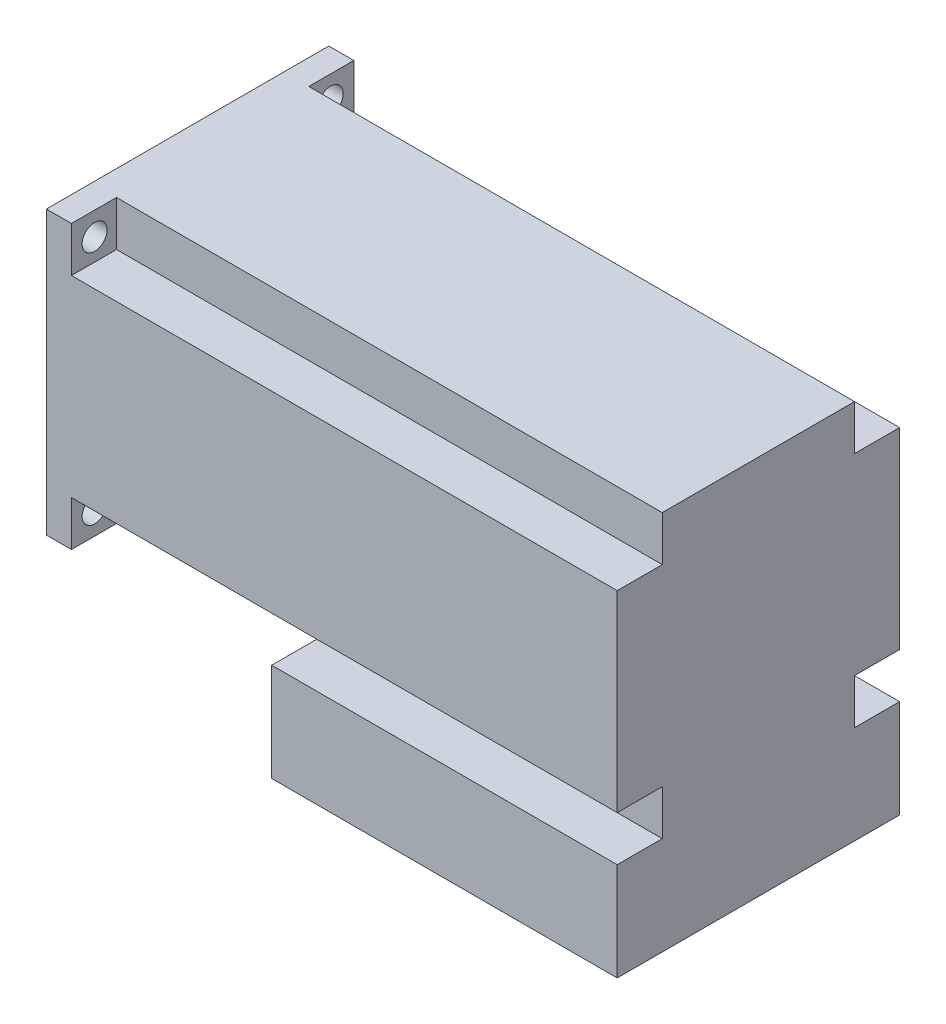
SolidWorks part; units mm, degrees
ref_plane "Front Plane" through (0, 0, 0) normal (0, 0, 1) x (1, 0, 0)
ref_plane "Top Plane" through (0, 0, 0) normal (0, 1, 0) x (1, 0, 0)
ref_plane "Right Plane" through (0, 0, 0) normal (1, 0, 0) x (0, 0, -1)
sketch "Sketch1" plane through (0, 0, 0) normal (0, 0, 1) x (1, 0, 0)
  line L0 (45, 0) -> (45, -19.6)
  line L1 (0, 0) -> (45, 0)
  line L2 (0, 0) -> (0, 56.4)
  line L3 (0, 56.4) -> (114, 56.4)
  line L4 (114, 0) -> (114, 56.4)
  line L5 (45, -19.6) -> (114, -19.6)
  line L6 (114, -19.6) -> (114, 0)
  dimension "D1" = 114
  dimension "D2" = 56.4
  dimension "D3" = 76
  dimension "D4" = 45
extrude "Boss-Extrude1" add sketch "Sketch1" along normal blind 56.4
sketch "Sketch2" plane through (0, 0, 0) normal (-1, 0, 0) x (0, 0, 1)
  line L0 (0, 28.2) -> (56.4, 28.2) construction
  line L1 (0, 56.4) -> (0, 0) construction
  line L2 (56.4, 56.4) -> (56.4, 0) construction
  line L3 (28.2, 28.2) -> (28.2, 0) construction
  line L4 (56.4, 0) -> (0, 0) construction
  circle A0 centre (4.63, 4.63) radius 2.5
  circle A1 centre (51.77, 4.63) radius 2.5
  circle A2 centre (51.77, 51.77) radius 2.5
  circle A3 centre (4.63, 51.77) radius 2.5
  dimension "D1" = 5
  dimension "D4" = 23.57
  dimension "D5" = 23.57
  dimension "D2" = 2
  dimension "D3" = 2
extrude "Cut-Extrude1" cut sketch "Sketch2" against normal blind 5
sketch "Sketch3" plane through (0, 0, 0) normal (-1, 0, 0) x (0, 0, 1)
  line L0 (0, 0) -> (56.4, 56.4) construction
  circle A0 centre (28.2, 28.2) radius 3.175
  dimension "D1" = 6.35
extrude "Boss-Extrude2" add sketch "Sketch3" along normal blind 20
sketch "Sketch4" plane through (114, 0, 0) normal (1, 0, 0) x (0, 0, -1)
  line L1 (-56.4, 56.4) -> (-47.4, 56.4)
  line L2 (-56.4, 56.4) -> (-56.4, 47.4)
  line L3 (-56.4, 47.4) -> (-47.4, 47.4)
  line L4 (-47.4, 56.4) -> (-47.4, 47.4)
  line L16 (-9, 56.4) -> (-9, 47.4)
  line L17 (-9, 56.4) -> (0, 56.4)
  line L18 (0, 56.4) -> (0, 47.4)
  line L19 (-9, 47.4) -> (0, 47.4)
  line L20 (-9, 9) -> (-9, 0)
  line L21 (-9, 9) -> (0, 9)
  line L22 (0, 9) -> (0, 0)
  line L23 (-9, 0) -> (0, 0)
  line L24 (-56.4, 9) -> (-56.4, 0)
  line L25 (-56.4, 9) -> (-47.4, 9)
  line L26 (-47.4, 9) -> (-47.4, 0)
  line L27 (-56.4, 0) -> (-47.4, 0)
  dimension "D3" = 9
  dimension "D4" = 9
  dimension "D1" = 2
  dimension "D2" = 2
extrude "Cut-Extrude2" cut sketch "Sketch4" against normal blind 109
